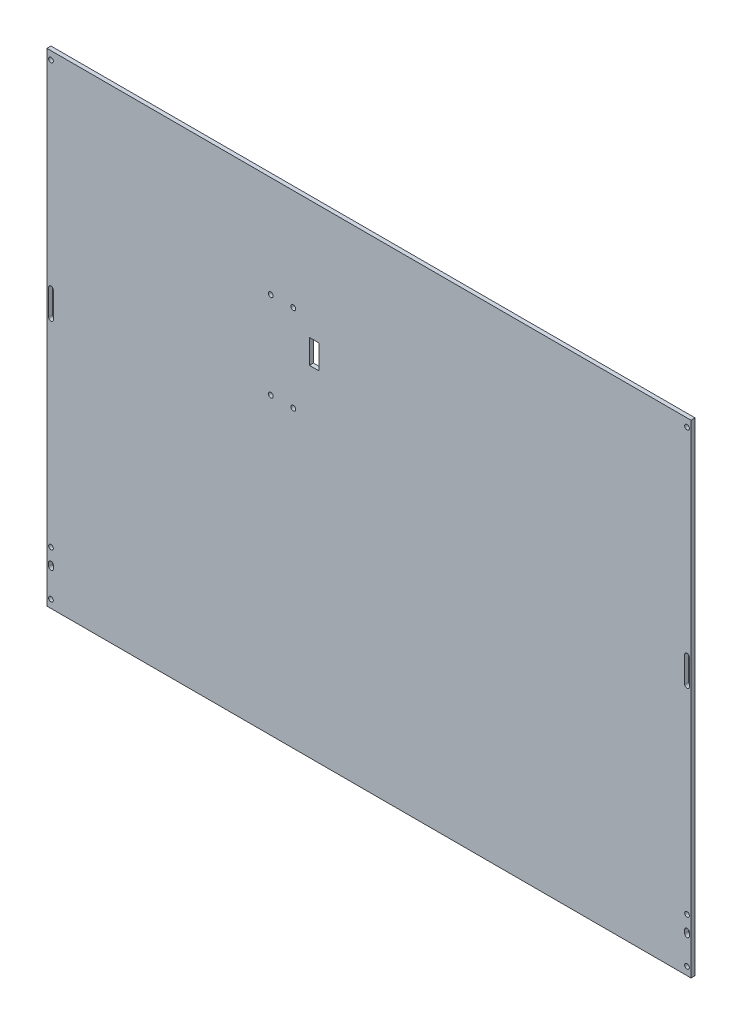
SolidWorks part; units mm, degrees
ref_plane "Front Plane" through (0, 0, 0) normal (0, 0, 1) x (1, 0, 0)
ref_plane "Top Plane" through (0, 0, 0) normal (0, 1, 0) x (1, 0, 0)
ref_plane "Right Plane" through (0, 0, 0) normal (1, 0, 0) x (0, 0, -1)
sketch "Sketch1" plane through (0, 0, 0) normal (0, 0, 1) x (1, 0, 0)
  line L1 (-254, -190.5) -> (254, -190.5)
  line L2 (-254, -190.5) -> (-254, 190.5)
  line L3 (-254, 190.5) -> (254, 190.5)
  line L4 (254, -190.5) -> (254, 190.5)
  line L5 (-254, -190.5) -> (254, 190.5) construction
  line L6 (-254, 190.5) -> (254, -190.5) construction
  point P0 (0, 0)
  dimension "D1" = 508
  dimension "D2" = 381
extrude "Boss-Extrude1" add sketch "Sketch1" along normal blind 3.175
sketch "Sketch3" plane through (0, 0, 3.175) normal (0, 0, 1) x (1, 0, 0)
  line L0 (-254, 190.5) -> (-254, -190.5) construction
  line L1 (-46.99, 77.47) -> (-39.37, 77.47)
  line L2 (-46.99, 77.47) -> (-46.99, 96.52)
  line L3 (-46.99, 96.52) -> (-39.37, 96.52)
  line L4 (-39.37, 77.47) -> (-39.37, 96.52)
  line L5 (254, 190.5) -> (-254, 190.5) construction
  dimension "D1" = 207.01
  dimension "D2" = 7.62
  dimension "D3" = 113.03
  dimension "D4" = 19.05
extrude "Cut-Extrude2" cut sketch "Sketch3" against normal up to surface (3.175 mm away) up to face at (0, 0, 0)
sketch "Sketch2" plane through (0, 0, 3.175) normal (0, 0, 1) x (1, 0, 0)
  line L0 (-250.825, 190.5) -> (-250.825, -190.5) construction
  line L1 (254, 190.5) -> (-254, 190.5) construction
  line L2 (-254, -190.5) -> (254, -190.5) construction
  line L3 (250.825, 23.4925) -> (250.825, -190.5) construction
  line L4 (254, -190.5) -> (254, 190.5) construction
  line L5 (-254, 190.5) -> (-254, -190.5) construction
  line L6 (0, 0) -> (0, -50000) construction
  line L8 (-39.37, 96.52) -> (-46.99, 96.52) construction
  line L9 (-250.825, 20.32) -> (-250.825, 27.94) construction
  line L10 (-250.825, 20.32) -> (-250.825, 27.94) construction
  line L11 (-252.6792, 20.32) -> (-252.6792, 27.94)
  line L12 (-248.9708, 20.32) -> (-248.9708, 27.94)
  line L13 (-250.825, 15.24) -> (-250.825, 7.62) construction
  line L14 (-248.9708, 15.24) -> (-248.9708, 7.62)
  line L15 (-252.6792, 15.24) -> (-252.6792, 7.62)
  line L16 (-252.6792, 20.32) -> (-252.6792, 15.24)
  line L17 (-248.9708, 20.32) -> (-248.9708, 15.24)
  line L18 (248.9708, 20.32) -> (248.9708, 27.94)
  line L19 (252.6792, 20.32) -> (252.6792, 27.94)
  line L20 (248.9708, 20.32) -> (248.9708, 15.24)
  line L21 (252.6792, 20.32) -> (252.6792, 15.24)
  line L22 (252.6792, 15.24) -> (252.6792, 7.62)
  line L23 (248.9708, 15.24) -> (248.9708, 7.62)
  line L24 (-250.825, -162.56) -> (-250.825, -160.02) construction
  line L25 (-252.6792, -162.56) -> (-252.6792, -160.02)
  line L26 (-248.9708, -162.56) -> (-248.9708, -160.02)
  line L27 (250.825, -162.56) -> (250.825, -160.02) construction
  line L28 (252.6792, -162.56) -> (252.6792, -160.02)
  line L29 (248.9708, -162.56) -> (248.9708, -160.02)
  circle A0 centre (-250.825, -184.15) radius 1.8542
  circle A1 centre (-250.825, 184.15) radius 1.8542
  circle A2 centre (250.825, 184.15) radius 1.8542
  circle A3 centre (250.825, -184.15) radius 1.8542
  arc A4 (-250.825, 22.2758) -> (-248.9708, 24.13) centre (-250.825, 24.13) ccw construction
  arc A5 (250.825, 22.2758) -> (252.6792, 24.13) centre (250.825, 24.13) ccw construction
  arc A6 (-250.825, 13.2842) -> (-250.825, 9.5758) centre (-250.825, 11.43) ccw construction
  circle A7 centre (-250.825, -148.59) radius 1.8542
  arc A8 (-250.825, -159.4358) -> (-252.6792, -161.29) centre (-250.825, -161.29) ccw construction
  arc A9 (248.9708, -161.29) -> (250.825, -159.4358) centre (250.825, -161.29) cw construction
  circle A10 centre (250.825, -148.59) radius 1.8542
  arc A11 (250.825, 13.2842) -> (252.6792, 11.43) centre (250.825, 11.43) cw construction
  circle A12 centre (-77.4887, 110.49) radius 1.905
  circle A13 centre (-77.4887, 41.91) radius 1.905
  circle A14 centre (-59.7087, 110.49) radius 1.905
  circle A15 centre (-59.7087, 41.91) radius 1.905
  arc A18 (-248.9708, 24.13) -> (-250.825, 25.9842) centre (-250.825, 24.13) ccw construction
  arc A19 (-250.825, 25.9842) -> (-252.6792, 24.13) centre (-250.825, 24.13) ccw construction
  arc A20 (-252.6792, 24.13) -> (-250.825, 22.2758) centre (-250.825, 24.13) ccw construction
  arc A21 (-252.6792, 20.32) -> (-250.825, 18.4658) centre (-250.825, 20.32) ccw construction
  arc A22 (-248.9708, 27.94) -> (-252.6792, 27.94) centre (-250.825, 27.94) ccw
  arc A23 (-250.825, 9.5758) -> (-250.825, 13.2842) centre (-250.825, 11.43) ccw construction
  arc A24 (-248.9708, 15.24) -> (-250.825, 17.0942) centre (-250.825, 15.24) ccw construction
  arc A25 (-252.6792, 7.62) -> (-248.9708, 7.62) centre (-250.825, 7.62) ccw
  arc A26 (-250.825, 18.4658) -> (-248.9708, 20.32) centre (-250.825, 20.32) ccw construction
  arc A27 (-250.825, 17.0942) -> (-252.6792, 15.24) centre (-250.825, 15.24) ccw construction
  arc A28 (248.9708, 27.94) -> (252.6792, 27.94) centre (250.825, 27.94) cw
  arc A29 (252.6792, 7.62) -> (248.9708, 7.62) centre (250.825, 7.62) cw
  arc A30 (248.9708, 11.43) -> (250.825, 13.2842) centre (250.825, 11.43) cw construction
  arc A31 (252.6792, 11.43) -> (250.825, 9.5758) centre (250.825, 11.43) cw construction
  arc A32 (250.825, 9.5758) -> (248.9708, 11.43) centre (250.825, 11.43) cw construction
  arc A33 (252.6792, 24.13) -> (248.9708, 24.13) centre (250.825, 24.13) ccw construction
  arc A34 (248.9708, 24.13) -> (250.825, 22.2758) centre (250.825, 24.13) ccw construction
  arc A35 (-252.6792, -162.56) -> (-248.9708, -162.56) centre (-250.825, -162.56) ccw
  arc A36 (-248.9708, -160.02) -> (-252.6792, -160.02) centre (-250.825, -160.02) ccw
  arc A37 (-248.9708, -161.29) -> (-250.825, -159.4358) centre (-250.825, -161.29) ccw construction
  arc A38 (-250.825, -163.1442) -> (-248.9708, -161.29) centre (-250.825, -161.29) ccw construction
  arc A39 (-252.6792, -161.29) -> (-250.825, -163.1442) centre (-250.825, -161.29) ccw construction
  arc A40 (252.6792, -162.56) -> (248.9708, -162.56) centre (250.825, -162.56) cw
  arc A41 (248.9708, -160.02) -> (252.6792, -160.02) centre (250.825, -160.02) cw
  arc A42 (250.825, -159.4358) -> (252.6792, -161.29) centre (250.825, -161.29) cw construction
  arc A43 (252.6792, -161.29) -> (250.825, -163.1442) centre (250.825, -161.29) cw construction
  arc A44 (250.825, -163.1442) -> (248.9708, -161.29) centre (250.825, -161.29) cw construction
  point P33 (0, -190.5)
  point P42 (-250.825, 24.13)
  point P54 (-250.825, 24.13)
  point P67 (-250.825, 11.43)
  point P76 (-250.825, -161.29)
  point P99 (250.825, -161.29)
  dimension "D3" = 3.7084
  dimension "D10" = 12.7
  dimension "D14" = 3.81
  dimension "D12" = 17.78
  dimension "D1" = 3.175
  dimension "D2" = 3.175
  dimension "D4" = 6.35
  dimension "D5" = 6.35
  dimension "D6" = 6.35
  dimension "D7" = 6.35
  dimension "D8" = 160.02
  dimension "D9" = 160.02
  dimension "D11" = 29.21
  dimension "D13" = 68.58
  dimension "D15" = 12.7187
  dimension "D16" = 13.97
  dimension "D17" = 3.7084
  dimension "D18" = 3.81
  dimension "D19" = 3.7084
  dimension "D20" = 3.81
  dimension "D21" = 3.81
  dimension "D22" = 3.7084
  dimension "D23" = 1.27
extrude "Cut-Extrude1" cut sketch "Sketch2" against normal blind 3.175
